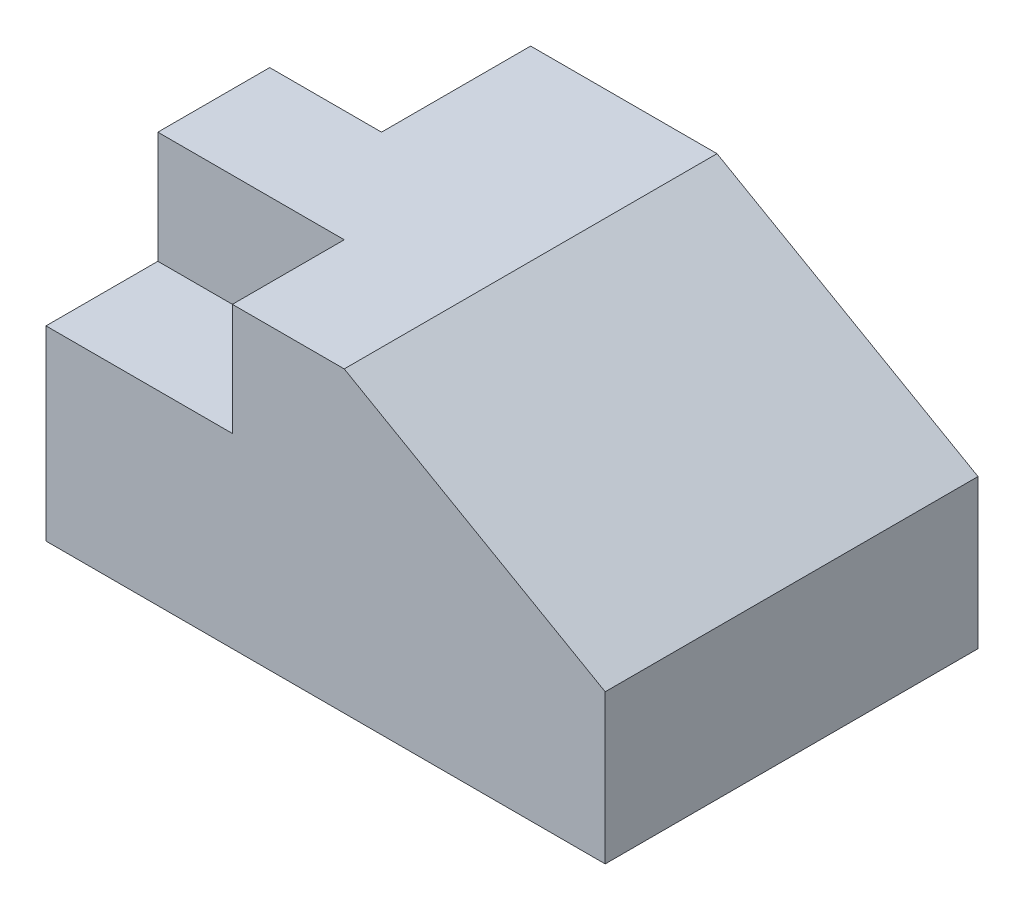
SolidWorks part; units mm, degrees
ref_plane "Front Plane" through (0, 0, 0) normal (0, 0, 1) x (1, 0, 0)
ref_plane "Top Plane" through (0, 0, 0) normal (0, 1, 0) x (1, 0, 0)
ref_plane "Right Plane" through (0, 0, 0) normal (1, 0, 0) x (0, 0, -1)
sketch "Sketch5" plane through (0, 0, 0) normal (0, 0, 1) x (1, 0, 0)
  line L0 (0, 0) -> (150, 0)
  line L1 (150, 0) -> (150, 40)
  line L2 (150, 40) -> (80, 80)
  line L7 (80, 80) -> (0, 80)
  line L8 (0, 80) -> (0, 0)
  dimension "D1" = 150
  dimension "D2" = 40
  dimension "D3" = 80
  dimension "D4" = 80
extrude "Boss-Extrude4" add sketch "Sketch5" against normal blind 100 contours L2 L7 L8 L0 L1
sketch "Sketch13" plane through (0, 0, 0) normal (0, 0, 1) x (1, 0, 0)
  line L1 (0, 80) -> (50, 80)
  line L2 (0, 80) -> (0, 50)
  line L3 (0, 50) -> (50, 50)
  line L4 (50, 80) -> (50, 50)
  dimension "D1" = 50
  dimension "D2" = 30
extrude "Cut-Extrude2" cut sketch "Sketch13" against normal blind 30
sketch "Sketch14" plane through (0, 80, 0) normal (0, 1, 0) x (1, 0, 0)
  line L1 (0, 100) -> (30, 100)
  line L2 (0, 100) -> (0, 60)
  line L3 (0, 60) -> (30, 60)
  line L4 (30, 100) -> (30, 60)
  dimension "D1" = 30
  dimension "D2" = 40
extrude "Cut-Extrude3" cut sketch "Sketch14" against normal through all
